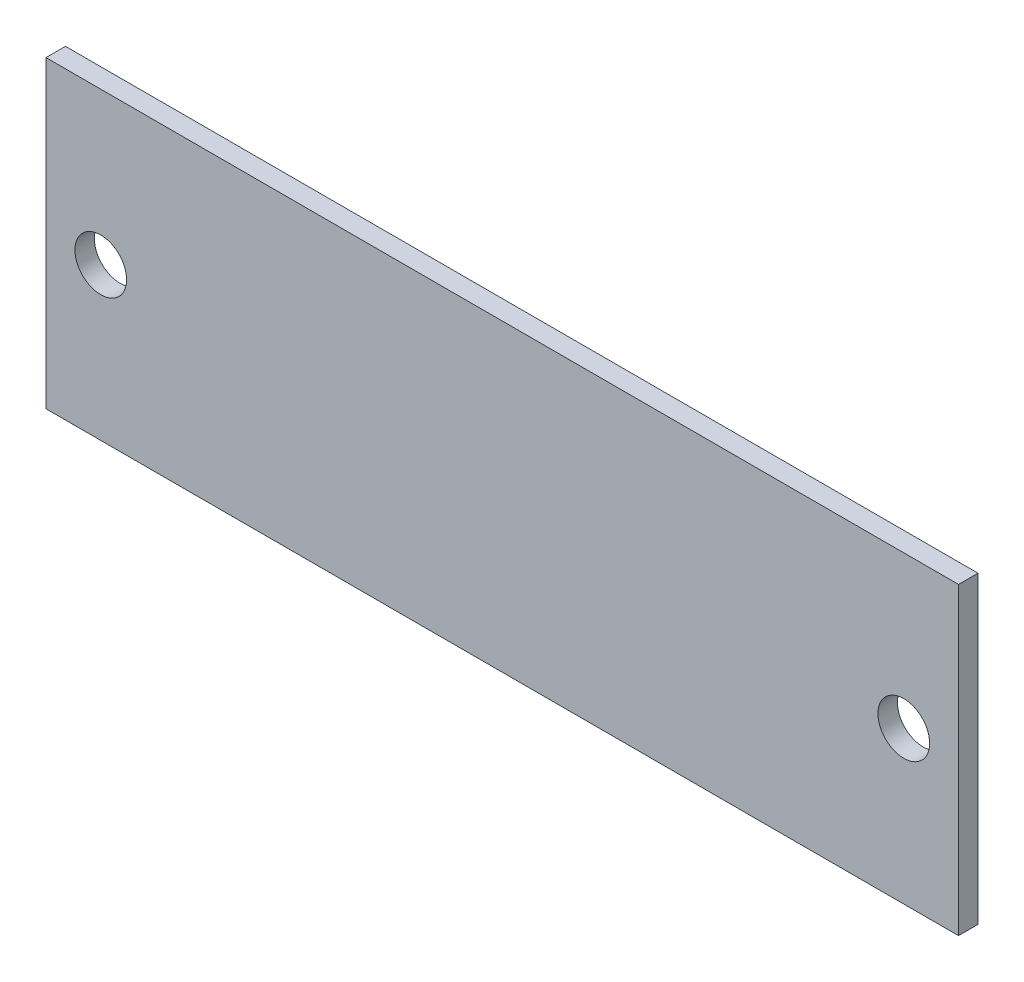
SolidWorks part; units mm, degrees
ref_plane "Front Plane" through (0, 0, 0) normal (0, 0, 1) x (1, 0, 0)
ref_plane "Top Plane" through (0, 0, 0) normal (0, 1, 0) x (1, 0, 0)
ref_plane "Right Plane" through (0, 0, 0) normal (1, 0, 0) x (0, 0, -1)
sketch "Sketch1" plane through (0, 0, 0) normal (0, 0, 1) x (1, 0, 0)
  line L0 (0, 0) -> (-38.1, 0) construction
  line L1 (-38.1, 0) -> (-38.1, 12.7) construction
  line L2 (-38.1, 12.7) -> (38.1, 12.7)
  line L3 (38.1, 12.7) -> (38.1, -12.7)
  line L4 (38.1, -12.7) -> (-38.1, -12.7)
  line L5 (-38.1, -12.7) -> (-38.1, 12.7)
  dimension "D1" = 38.1
  dimension "D2" = 12.7
  dimension "D3" = 76.2
  dimension "D4" = 25.4
extrude "Boss-Extrude1" add sketch "Sketch1" against normal blind 1.6256
sketch "Sketch2" plane through (0, 0, 0) normal (0, 0, 1) x (1, 0, 0)
  line L0 (38.1, 0) -> (33.528, 0) construction
  line L1 (38.1, -12.7) -> (38.1, 12.7) construction
  line L2 (0, 0) -> (0, 22.2427) construction
  circle A0 centre (33.528, 0) radius 2.159
  circle A1 centre (-33.528, 0) radius 2.159
  dimension "D2" = 4.318
  dimension "D1" = 4.572
extrude "Cut-Extrude1" cut sketch "Sketch2" against normal through all
